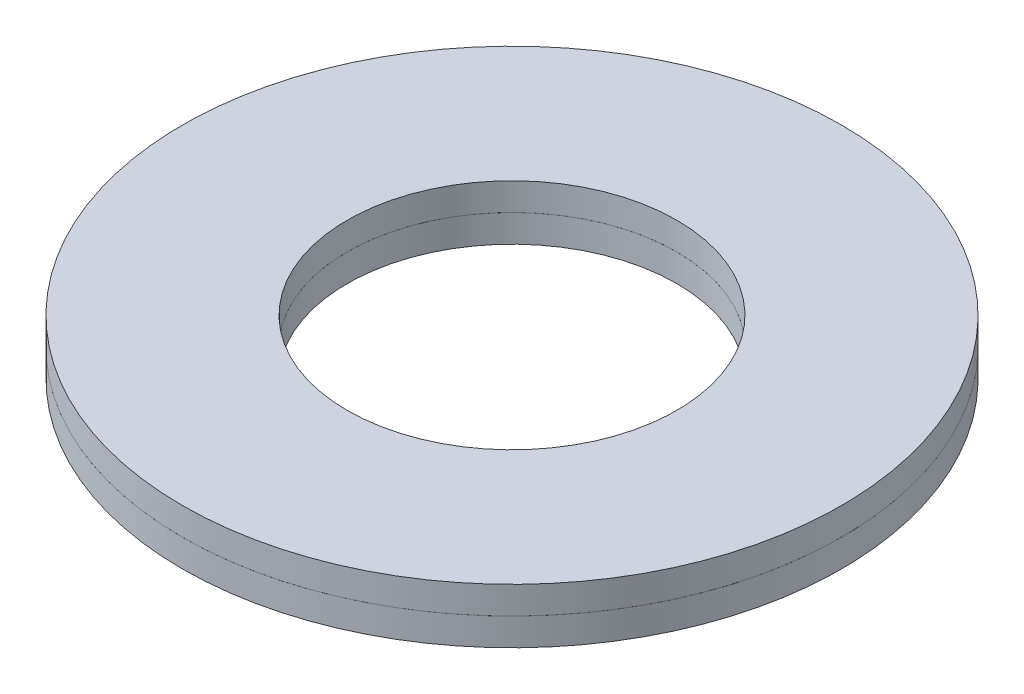
SolidWorks part; units mm, degrees
ref_plane "Front Plane" through (0, 0, 0) normal (0, 0, 1) x (1, 0, 0)
ref_plane "Top Plane" through (0, 0, 0) normal (0, 1, 0) x (1, 0, 0)
ref_plane "Right Plane" through (0, 0, 0) normal (1, 0, 0) x (0, 0, -1)
sketch "Sketch1" plane through (0, 0, 0) normal (1, 0, 0) x (0, 0, -1)
  line L0 (0, 64.8981) -> (0, -60.7111) construction
  line L1 (-60, 10.005) -> (-60, 0.005)
  line L2 (-60, 0.005) -> (-120, 0.005)
  line L3 (-120, 0.005) -> (-120, 10.005)
  line L4 (-120, 10.005) -> (-60, 10.005)
  line L5 (-120, -0.005) -> (-60, -0.005)
  line L6 (-120, -0.005) -> (-120, -10.005)
  line L7 (-120, -10.005) -> (-60, -10.005)
  line L8 (-60, -10.005) -> (-60, -0.005)
  line L9 (-60, 10.005) -> (-60, -10.005) construction
  point P9 (-60, 0)
  dimension "D1" = 10
  dimension "D2" = 120
  dimension "D3" = 0.01
  dimension "D4" = 60
revolve "Revolve1" add sketch "Sketch1" angle 360 about L0
